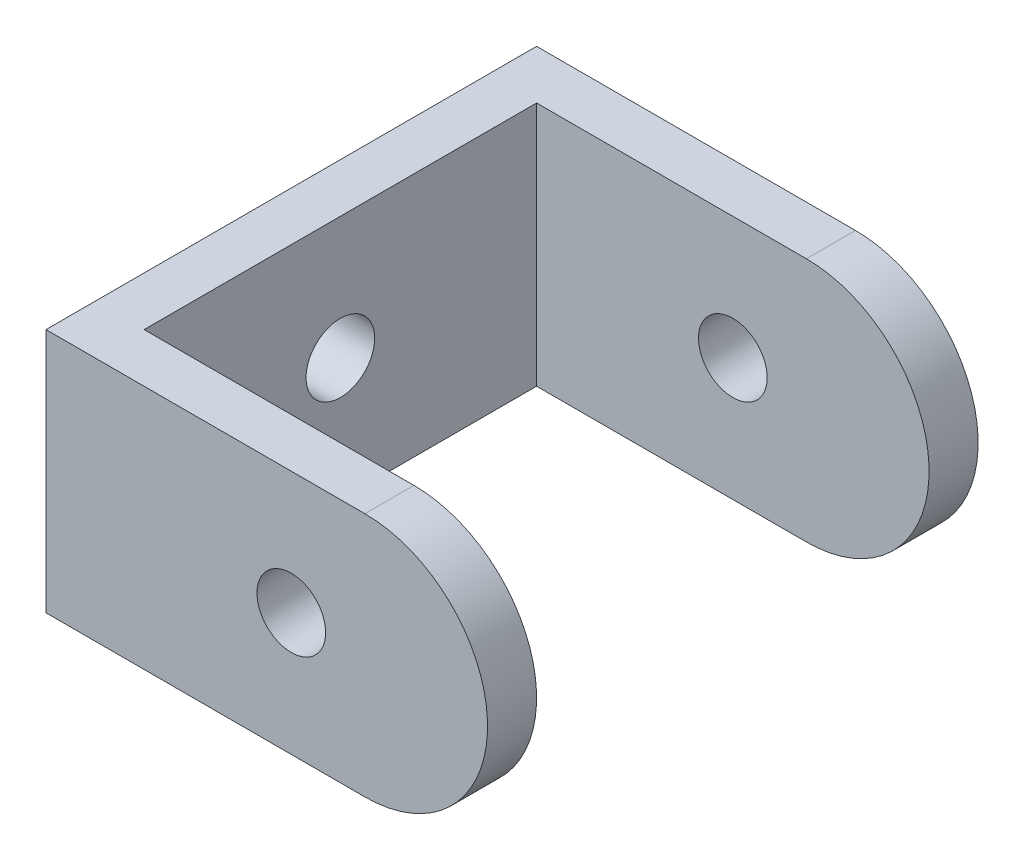
SolidWorks part; units mm, degrees
ref_plane "Front Plane" through (0, 0, 0) normal (0, 0, 1) x (1, 0, 0)
ref_plane "Top Plane" through (0, 0, 0) normal (0, 1, 0) x (1, 0, 0)
ref_plane "Right Plane" through (0, 0, 0) normal (1, 0, 0) x (0, 0, -1)
sketch "Sketch1" plane through (0, 0, 0) normal (0, 1, 0) x (1, 0, 0)
  line L0 (20, -20) -> (20, 20)
  line L1 (-25, -25) -> (25, -25)
  line L2 (-25, -25) -> (-25, 25)
  line L3 (-25, 25) -> (25, 25)
  line L4 (25, -25) -> (25, 25)
  line L5 (-25, -25) -> (25, 25) construction
  line L6 (-25, 25) -> (25, -25) construction
  line L7 (-20, 20) -> (20, 20)
  line L8 (-20, -20) -> (-20, 20)
  line L9 (-20, -20) -> (20, -20)
  point P0 (0, 0)
  dimension "D1" = 50
  dimension "D2" = 50
  dimension "D3" = 5
extrude "Boss-Extrude1" add sketch "Sketch1" along normal blind 25
sketch "Sketch2" plane through (25, 0, 0) normal (1, 0, 0) x (0, 0, -1)
  line L0 (-25, 0) -> (25, 0) construction
  line L1 (25, 25) -> (25, 0) construction
  circle A0 centre (0, 12.5) radius 3.5
  dimension "D3" = 7
  dimension "D1" = 12.5
  dimension "D2" = 25
extrude "Cut-Extrude1" cut sketch "Sketch2" against normal blind 55
sketch "Sketch3" plane through (0, 0, 25) normal (0, 0, 1) x (1, 0, 0)
  line L0 (-25, 0) -> (25, 0) construction
  line L1 (25, 25) -> (25, 0) construction
  circle A0 centre (0, 12.5) radius 3.5
  dimension "D3" = 7
  dimension "D1" = 12.5
  dimension "D2" = 25
extrude "Cut-Extrude2" cut sketch "Sketch3" against normal blind 55
sketch "Sketch4" plane through (0, 0, 25) normal (0, 0, 1) x (1, 0, 0)
  line L0 (-25, 25) -> (25, 25) construction
  line L1 (-25, 0) -> (25, 0) construction
  line L2 (7.5, 25) -> (25, 25)
  line L3 (25, 25) -> (25, 0)
  line L4 (25, 0) -> (7.5, 0)
  arc A1 (7.5, 25) -> (7.5, 0) centre (7.5, 12.5) cw
  point P3 (20, 12.5)
  line M4 (25, 25) -> (-25, 25)
  dimension "D1" = 20
extrude "Cut-Extrude3" cut sketch "Sketch4" against normal through all contours A1 L3 M4
sketch "Sketch5" plane through (-20, 0, 0) normal (1, 0, 0) x (0, 0, -1)
  line L1 (20, 25) -> (-20, 25)
  line L2 (20, 25) -> (20, 0)
  line L3 (20, 0) -> (-20, 0)
  line L4 (-20, 25) -> (-20, 0)
extrude "Cut-Extrude4" [suppressed] cut sketch "Sketch5" along normal blind 64
